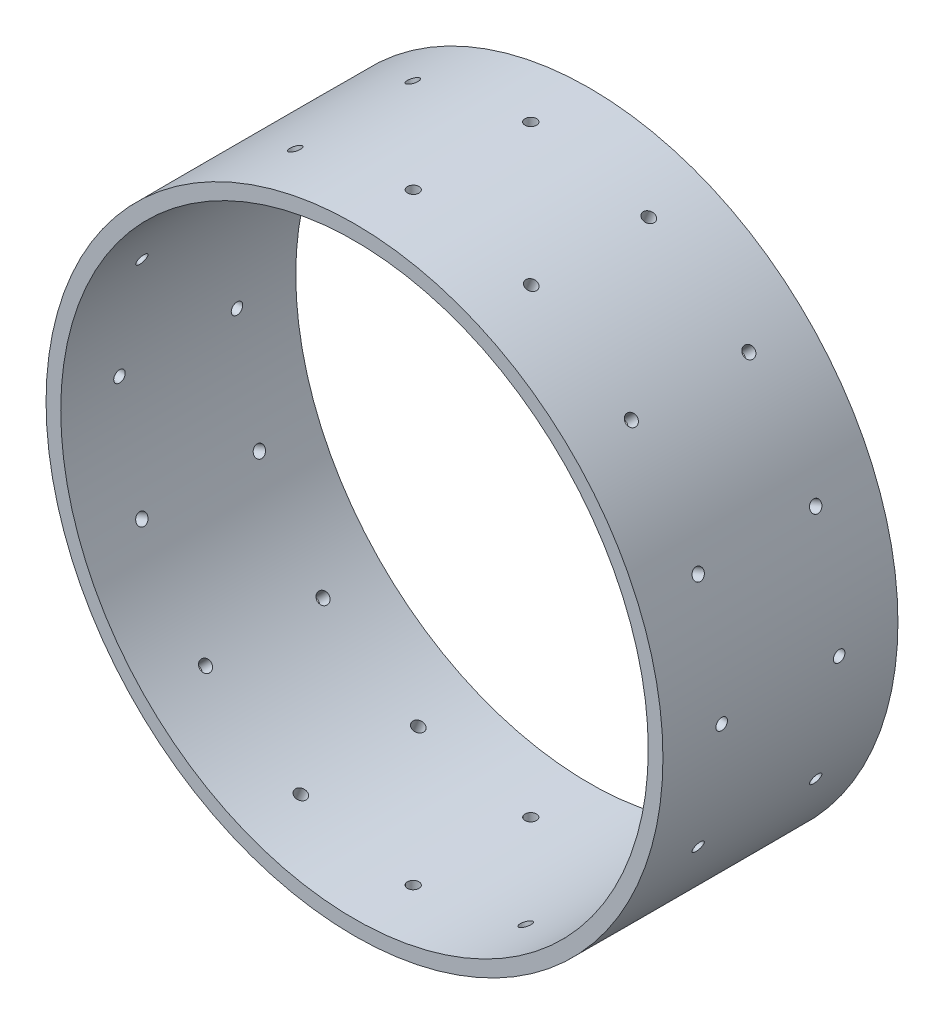
SolidWorks part; units mm, degrees
material "6061-T6 (SS)"
ref_plane "Front Plane" through (0, 0, 0) normal (0, 0, 1) x (1, 0, 0)
ref_plane "Top Plane" through (0, 0, 0) normal (0, 1, 0) x (1, 0, 0)
ref_plane "Right Plane" through (0, 0, 0) normal (1, 0, 0) x (0, 0, -1)
sketch "Sketch1" plane through (0, 0, 0) normal (0, 0, 1) x (1, 0, 0)
  circle A0 centre (0, 0) radius 63.5
  circle A1 centre (0, 0) radius 66.675
extrude "Extrude1" add sketch "Sketch1" along normal blind 50.8
ref_plane "Plane1" through (0, 0, 12.7) normal (0, 0, -1) x (-1, 0, 0)
sketch "Sketch2" plane through (0, 0, 12.7) normal (0, 0, -1) x (-1, 0, 0)
  line L0 (0, 0) -> (0, 66.675) construction
  line L1 (0, 0) -> (13.0076, 65.3939) construction
  circle A0 centre (0, 0) radius 66.675 construction
  dimension "D1" = 11.25
ref_plane "Plane4" through (0, 66.675, 12.7) normal (0, 1, 0) x (-1, 0, 0)
sketch "Sketch7" plane through (0, 66.675, 12.7) normal (0, 1, 0) x (-1, 0, 0)
  line L0 (0, 0) -> (0, 25.4) construction
hole_wizard "#40 (0.098) Diameter Hole2" positions "Sketch9" profile "Sketch8" hole size "#40" standard "Ansi Inch"
sketch "Sketch9" plane through (0, 66.675, 12.7) normal (0, 1, 0) x (-1, 0, 0)
  point P1 (0, 0)
  point P4 (0, 25.4)
sketch "Sketch8" plane through (0, 66.675, 12.7) normal (1, 0, 0) x (0, 0, 1)
  line L0 (0, 0) -> (0, 13.4478)
  line L1 (0, 13.4478) -> (1.2446, 12.7)
  line L2 (1.2446, 12.7) -> (1.2446, 0)
  line L5 (1.2446, 0) -> (0, 0)
  line L10 (0, 13.4478) -> (-1.2446, 12.7) construction
  line L11 (0, -6.35) -> (0, 107.95) construction
  dimension "Hole Dia." = 2.4892
  dimension "Hole Depth" = 12.7
  dimension "Drill Angle" = 118
pattern_circular "CirPattern1" count 16 over 360 about axis through (0, 0, 50.8) along (0, 0, -1) of "#40 (0.098) Diameter Hole2"
ref_plane "Plane5" through (-13.0076, 65.3939, 12.7) normal (-0.1951, 0.9808, 0) x (-0.9808, -0.1951, 0)
hole_wizard "3/8 Clearance Hole1" [suppressed] positions "Sketch13" profile "Sketch14" hole size "3/8" standard "Ansi Inch"
sketch "Sketch13" plane through (-13.0076, 65.3939, 12.7) normal (-0.1951, 0.9808, 0) x (-0.9808, -0.1951, 0)
  point P1 (0, 0)
sketch "Sketch14" plane through (-13.0076, 65.3939, 12.7) normal (0, 0, 1) x (-0.9808, -0.1951, 0)
  line L0 (0, 0) -> (0, 15.9835)
  line L1 (0, 15.9835) -> (5.0419, 12.954)
  line L2 (5.0419, 12.954) -> (5.0419, 3.175)
  line L3 (5.0419, 3.175) -> (8.2169, 0)
  line L5 (8.2169, 0) -> (0, 0)
  line L6 (-5.0419, 3.175) -> (-8.2169, 0) construction
  line L10 (0, 15.9835) -> (-5.0419, 12.954) construction
  line L11 (0, -6.35) -> (0, 107.95) construction
  dimension "Hole Dia." = 10.0838
  dimension "Hole Depth" = 12.954
  dimension "Near C'Sink Dia." = 16.4338
  dimension "Near C'Sink Angle" = 90
  dimension "Drill Angle" = 118
ref_plane "Plane6" through (0, 0, 12.7) normal (-0.1951, 0.9808, 0) x (-0.9808, -0.1951, 0)
mirror "Mirror1" [suppressed] about plane through (0, 0, 12.7) normal (-0.1951, 0.9808, 0)
